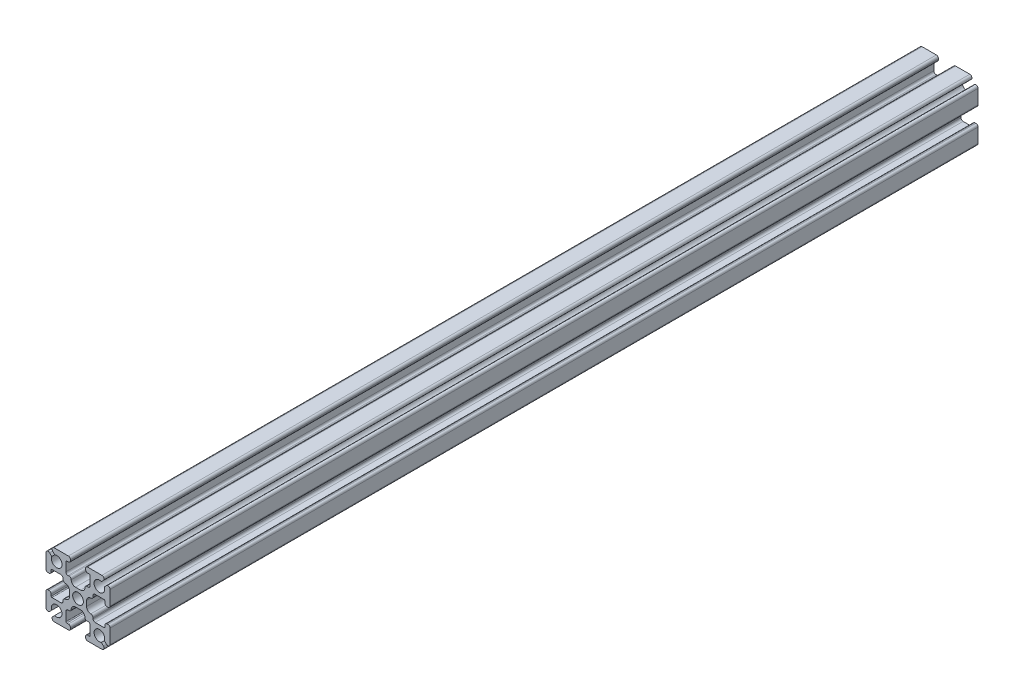
SolidWorks part; units mm, degrees
ref_plane "Front" through (0, 0, 0) normal (0, 0, 1) x (1, 0, 0)
ref_plane "Top" through (0, 0, 0) normal (0, 1, 0) x (1, 0, 0)
ref_plane "Right" through (0, 0, 0) normal (1, 0, 0) x (0, 0, -1)
sketch "Sketch1" plane through (0, 0, 0) normal (0, 0, 1) x (1, 0, 0)
  line L0 (6.6464, 5.9393) -> (6.1636, 5.4565)
  line L1 (5.4565, 6.1636) -> (5.9393, 6.6464)
  line L2 (5.5858, 7.5) -> (2.25, 7.5)
  line L3 (1.75, 7) -> (1.75, 6.8)
  line L4 (2.25, 6.3) -> (2.65, 6.3)
  line L5 (2.85, 6.1) -> (2.85, 4)
  line L6 (2.35, 3.5) -> (2.1, 3.5)
  line L7 (0.6, 2) -> (-0.6, 2)
  line L8 (-2.1, 3.5) -> (-2.35, 3.5)
  line L9 (-2.85, 4) -> (-2.85, 6.1)
  line L10 (-2.65, 6.3) -> (-2.25, 6.3)
  line L11 (-1.75, 6.8) -> (-1.75, 7)
  line L12 (-2.25, 7.5) -> (-5.5858, 7.5)
  line L13 (-5.9393, 6.6464) -> (-5.4565, 6.1636)
  line L14 (-6.1636, 5.4565) -> (-6.6464, 5.9393)
  line L15 (-7.5, 5.5858) -> (-7.5, 2.25)
  line L16 (-7, 1.75) -> (-6.8, 1.75)
  line L17 (-6.3, 2.25) -> (-6.3, 2.65)
  line L18 (-6.1, 2.85) -> (-4, 2.85)
  line L19 (-3.5, 2.35) -> (-3.5, 2.1)
  line L20 (-2, 0.6) -> (-2, -0.6)
  line L21 (-3.5, -2.1) -> (-3.5, -2.35)
  line L22 (-4, -2.85) -> (-6.1, -2.85)
  line L23 (-6.3, -2.65) -> (-6.3, -2.25)
  line L24 (-6.8, -1.75) -> (-7, -1.75)
  line L25 (-7.5, -2.25) -> (-7.5, -5.5858)
  line L26 (-6.6464, -5.9393) -> (-6.1636, -5.4565)
  line L27 (-5.4565, -6.1636) -> (-5.9393, -6.6464)
  line L28 (-5.5858, -7.5) -> (-2.25, -7.5)
  line L29 (-1.75, -7) -> (-1.75, -6.8)
  line L30 (-2.25, -6.3) -> (-2.65, -6.3)
  line L31 (-2.85, -6.1) -> (-2.85, -4)
  line L32 (-2.35, -3.5) -> (-2.1, -3.5)
  line L33 (-0.6, -2) -> (0.6, -2)
  line L34 (2.1, -3.5) -> (2.35, -3.5)
  line L35 (2.85, -4) -> (2.85, -6.1)
  line L36 (2.65, -6.3) -> (2.25, -6.3)
  line L37 (1.75, -6.8) -> (1.75, -7)
  line L38 (2.25, -7.5) -> (5.5858, -7.5)
  line L39 (5.9393, -6.6464) -> (5.4565, -6.1636)
  line L40 (6.1636, -5.4565) -> (6.6464, -5.9393)
  line L41 (7.5, -5.5858) -> (7.5, -2.25)
  line L42 (7, -1.75) -> (6.8, -1.75)
  line L43 (6.3, -2.25) -> (6.3, -2.65)
  line L44 (6.1, -2.85) -> (4, -2.85)
  line L45 (3.5, -2.35) -> (3.5, -2.1)
  line L46 (2, -0.6) -> (2, 0.6)
  line L47 (3.5, 2.1) -> (3.5, 2.35)
  line L48 (4, 2.85) -> (6.1, 2.85)
  line L49 (6.3, 2.65) -> (6.3, 2.25)
  line L50 (6.8, 1.75) -> (7, 1.75)
  line L51 (7.5, 2.25) -> (7.5, 5.5858)
  circle A0 centre (0, 0) radius 1.25
  arc A1 (6.1636, 5.4565) -> (5.4565, 6.1636) centre (5, 5) cw
  arc A2 (5.9393, 6.6464) -> (5.5858, 7.5) centre (5.5858, 7) ccw
  arc A3 (2.25, 7.5) -> (1.75, 7) centre (2.25, 7) ccw
  arc A4 (1.75, 6.8) -> (2.25, 6.3) centre (2.25, 6.8) ccw
  arc A5 (2.65, 6.3) -> (2.85, 6.1) centre (2.65, 6.1) cw
  arc A6 (2.85, 4) -> (2.35, 3.5) centre (2.35, 4) cw
  arc A7 (2.1, 3.5) -> (1.6, 3) centre (2.1, 3) ccw
  arc A8 (1.6, 3) -> (0.6, 2) centre (0.6, 3) cw
  arc A9 (-0.6, 2) -> (-1.6, 3) centre (-0.6, 3) cw
  arc A10 (-1.6, 3) -> (-2.1, 3.5) centre (-2.1, 3) ccw
  arc A11 (-2.35, 3.5) -> (-2.85, 4) centre (-2.35, 4) cw
  arc A12 (-2.85, 6.1) -> (-2.65, 6.3) centre (-2.65, 6.1) cw
  arc A13 (-2.25, 6.3) -> (-1.75, 6.8) centre (-2.25, 6.8) ccw
  arc A14 (-1.75, 7) -> (-2.25, 7.5) centre (-2.25, 7) ccw
  arc A15 (-5.5858, 7.5) -> (-5.9393, 6.6464) centre (-5.5858, 7) ccw
  arc A16 (-5.4565, 6.1636) -> (-6.1636, 5.4565) centre (-5, 5) cw
  arc A17 (-6.6464, 5.9393) -> (-7.5, 5.5858) centre (-7, 5.5858) ccw
  arc A18 (-7.5, 2.25) -> (-7, 1.75) centre (-7, 2.25) ccw
  arc A19 (-6.8, 1.75) -> (-6.3, 2.25) centre (-6.8, 2.25) ccw
  arc A20 (-6.3, 2.65) -> (-6.1, 2.85) centre (-6.1, 2.65) cw
  arc A21 (-4, 2.85) -> (-3.5, 2.35) centre (-4, 2.35) cw
  arc A22 (-3.5, 2.1) -> (-3, 1.6) centre (-3, 2.1) ccw
  arc A23 (-3, 1.6) -> (-2, 0.6) centre (-3, 0.6) cw
  arc A24 (-2, -0.6) -> (-3, -1.6) centre (-3, -0.6) cw
  arc A25 (-3, -1.6) -> (-3.5, -2.1) centre (-3, -2.1) ccw
  arc A26 (-3.5, -2.35) -> (-4, -2.85) centre (-4, -2.35) cw
  arc A27 (-6.1, -2.85) -> (-6.3, -2.65) centre (-6.1, -2.65) cw
  arc A28 (-6.3, -2.25) -> (-6.8, -1.75) centre (-6.8, -2.25) ccw
  arc A29 (-7, -1.75) -> (-7.5, -2.25) centre (-7, -2.25) ccw
  arc A30 (-7.5, -5.5858) -> (-6.6464, -5.9393) centre (-7, -5.5858) ccw
  arc A31 (-6.1636, -5.4565) -> (-5.4565, -6.1636) centre (-5, -5) cw
  arc A32 (-5.9393, -6.6464) -> (-5.5858, -7.5) centre (-5.5858, -7) ccw
  arc A33 (-2.25, -7.5) -> (-1.75, -7) centre (-2.25, -7) ccw
  arc A34 (-1.75, -6.8) -> (-2.25, -6.3) centre (-2.25, -6.8) ccw
  arc A35 (-2.65, -6.3) -> (-2.85, -6.1) centre (-2.65, -6.1) cw
  arc A36 (-2.85, -4) -> (-2.35, -3.5) centre (-2.35, -4) cw
  arc A37 (-2.1, -3.5) -> (-1.6, -3) centre (-2.1, -3) ccw
  arc A38 (-1.6, -3) -> (-0.6, -2) centre (-0.6, -3) cw
  arc A39 (0.6, -2) -> (1.6, -3) centre (0.6, -3) cw
  arc A40 (1.6, -3) -> (2.1, -3.5) centre (2.1, -3) ccw
  arc A41 (2.35, -3.5) -> (2.85, -4) centre (2.35, -4) cw
  arc A42 (2.85, -6.1) -> (2.65, -6.3) centre (2.65, -6.1) cw
  arc A43 (2.25, -6.3) -> (1.75, -6.8) centre (2.25, -6.8) ccw
  arc A44 (1.75, -7) -> (2.25, -7.5) centre (2.25, -7) ccw
  arc A45 (5.5858, -7.5) -> (5.9393, -6.6464) centre (5.5858, -7) ccw
  arc A46 (5.4565, -6.1636) -> (6.1636, -5.4565) centre (5, -5) cw
  arc A47 (6.6464, -5.9393) -> (7.5, -5.5858) centre (7, -5.5858) ccw
  arc A48 (7.5, -2.25) -> (7, -1.75) centre (7, -2.25) ccw
  arc A49 (6.8, -1.75) -> (6.3, -2.25) centre (6.8, -2.25) ccw
  arc A50 (6.3, -2.65) -> (6.1, -2.85) centre (6.1, -2.65) cw
  arc A51 (4, -2.85) -> (3.5, -2.35) centre (4, -2.35) cw
  arc A52 (3.5, -2.1) -> (3, -1.6) centre (3, -2.1) ccw
  arc A53 (3, -1.6) -> (2, -0.6) centre (3, -0.6) cw
  arc A54 (2, 0.6) -> (3, 1.6) centre (3, 0.6) cw
  arc A55 (3, 1.6) -> (3.5, 2.1) centre (3, 2.1) ccw
  arc A56 (3.5, 2.35) -> (4, 2.85) centre (4, 2.35) cw
  arc A57 (6.1, 2.85) -> (6.3, 2.65) centre (6.1, 2.65) cw
  arc A58 (6.3, 2.25) -> (6.8, 1.75) centre (6.8, 2.25) ccw
  arc A59 (7, 1.75) -> (7.5, 2.25) centre (7, 2.25) ccw
  arc A60 (7.5, 5.5858) -> (6.6464, 5.9393) centre (7, 5.5858) ccw
extrude "Boss-Extrude1" add sketch "Sketch1" along normal blind 203.2
